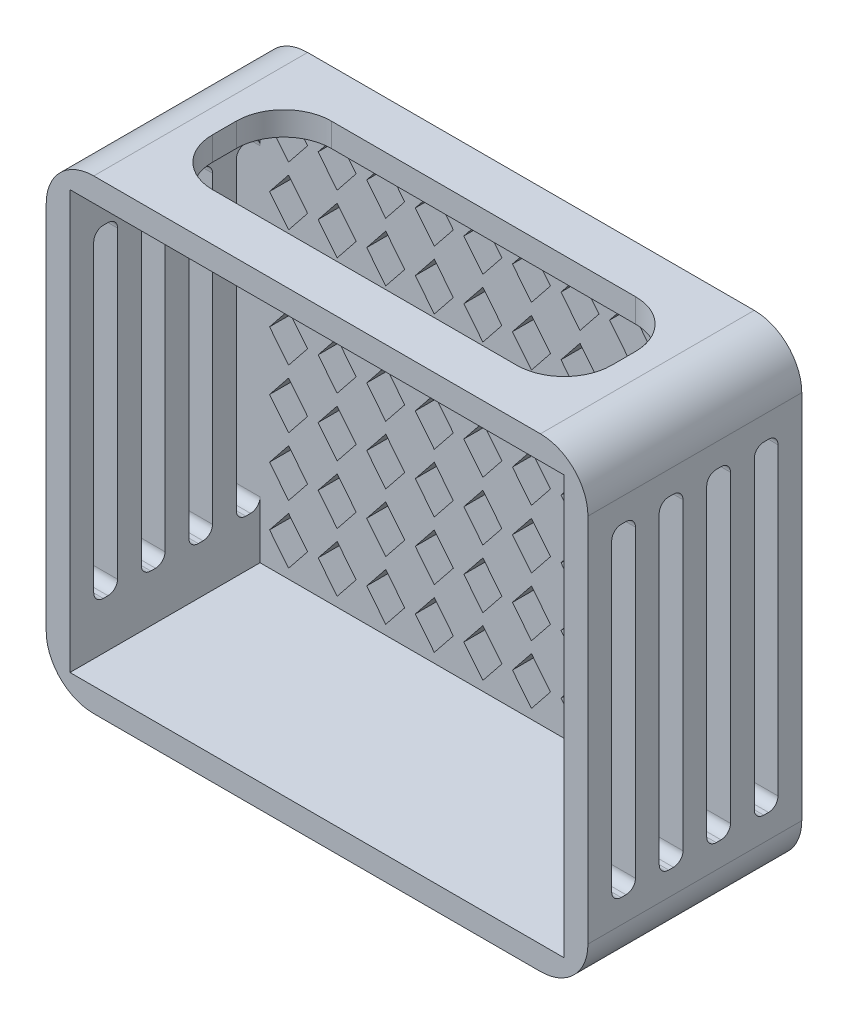
SolidWorks part; units mm, degrees
ref_plane "前视基准面" through (0, 0, 0) normal (0, 0, 1) x (1, 0, 0)
ref_plane "上视基准面" through (0, 0, 0) normal (0, 1, 0) x (1, 0, 0)
ref_plane "右视基准面" through (0, 0, 0) normal (1, 0, 0) x (0, 0, -1)
other "Configuration Table"
sketch "草图1" plane through (0, 0, 0) normal (0, 0, 1) x (1, 0, 0)
  line L1 (0, 98) -> (114, 98)
  line L2 (0, 98) -> (0, 0)
  line L3 (0, 0) -> (114, 0)
  line L4 (114, 98) -> (114, 0)
extrude "凸台-拉伸2" add sketch "草图1" against normal blind 45 contours L2 L1 L4 L3
sketch "草图3" plane through (0, 0, 0) normal (0, 0, 1) x (1, 0, 0)
  line L1 (5, 93) -> (109, 93)
  line L2 (5, 93) -> (5, 5)
  line L3 (5, 5) -> (109, 5)
  line L4 (109, 93) -> (109, 5)
  point P4 (0, 0)
extrude "切除-拉伸2" cut sketch "草图3" against normal blind 40
fillet "圆角1" radius 10 1 edges at (0, 98, -22.5)
fillet "圆角2" radius 10 1 edges at (0, 0, -22.5)
fillet "圆角3" radius 10 1 edges at (114, 0, -22.5)
fillet "圆角4" radius 10 1 edges at (114, 98, -22.5)
sketch "草图4" plane through (0, 98, 0) normal (0, 1, 0) x (1, 0, 0)
  line L0 (10, 45) -> (10, 0) construction
  line L1 (25, 35) -> (89, 35)
  line L2 (15, 25) -> (15, 20)
  line L3 (25, 10) -> (89, 10)
  line L4 (99, 25) -> (99, 20)
  line L5 (10, 45) -> (104, 45) construction
  line L6 (10, 0) -> (104, 0) construction
  line L7 (104, 0) -> (104, 45) construction
  arc A0 (99, 20) -> (89, 10) centre (89, 20) cw
  arc A1 (99, 25) -> (89, 35) centre (89, 25) ccw
  arc A2 (25, 10) -> (15, 20) centre (25, 20) cw
  arc A3 (25, 35) -> (15, 25) centre (25, 25) ccw
  dimension "D6" = 10
  dimension "D1" = 5
  dimension "D2" = 5
  dimension "D3" = 10
  dimension "D4" = 45
  dimension "D5" = 10
sketch "草图5" plane through (0, 0, -45) normal (0, 0, -1) x (-1, 0, 0)
  line L4 (-103, 91) -> (-107, 86)
  line L5 (-107, 86) -> (-103, 81)
  line L6 (-103, 81) -> (-99, 86)
  line L7 (-99, 86) -> (-103, 91)
  line L8 (-114, 88) -> (-114, 10) construction
  line L9 (0, 88) -> (0, 10) construction
  line L10 (-10, 98) -> (-104, 98) construction
  line L11 (-10, 0) -> (-104, 0) construction
  line L12 (-92.7778, 91) -> (-96.7778, 86)
  line L13 (-88.7778, 86) -> (-92.7778, 91)
  line L14 (-96.7778, 86) -> (-92.7778, 81)
  line L15 (-92.7778, 81) -> (-88.7778, 86)
  line L16 (-82.5556, 91) -> (-86.5556, 86)
  line L17 (-78.5556, 86) -> (-82.5556, 91)
  line L18 (-86.5556, 86) -> (-82.5556, 81)
  line L19 (-82.5556, 81) -> (-78.5556, 86)
  line L20 (-72.3333, 91) -> (-76.3333, 86)
  line L21 (-68.3333, 86) -> (-72.3333, 91)
  line L22 (-76.3333, 86) -> (-72.3333, 81)
  line L23 (-72.3333, 81) -> (-68.3333, 86)
  line L24 (-62.1111, 91) -> (-66.1111, 86)
  line L25 (-58.1111, 86) -> (-62.1111, 91)
  line L26 (-66.1111, 86) -> (-62.1111, 81)
  line L27 (-62.1111, 81) -> (-58.1111, 86)
  line L28 (-51.8889, 91) -> (-55.8889, 86)
  line L29 (-47.8889, 86) -> (-51.8889, 91)
  line L30 (-55.8889, 86) -> (-51.8889, 81)
  line L31 (-51.8889, 81) -> (-47.8889, 86)
  line L32 (-41.6667, 91) -> (-45.6667, 86)
  line L33 (-37.6667, 86) -> (-41.6667, 91)
  line L34 (-45.6667, 86) -> (-41.6667, 81)
  line L35 (-41.6667, 81) -> (-37.6667, 86)
  line L36 (-31.4444, 91) -> (-35.4444, 86)
  line L37 (-27.4444, 86) -> (-31.4444, 91)
  line L38 (-35.4444, 86) -> (-31.4444, 81)
  line L39 (-31.4444, 81) -> (-27.4444, 86)
  line L40 (-21.2222, 91) -> (-25.2222, 86)
  line L41 (-17.2222, 86) -> (-21.2222, 91)
  line L42 (-25.2222, 86) -> (-21.2222, 81)
  line L43 (-21.2222, 81) -> (-17.2222, 86)
  line L44 (-11, 91) -> (-15, 86)
  line L45 (-7, 86) -> (-11, 91)
  line L46 (-15, 86) -> (-11, 81)
  line L47 (-11, 81) -> (-7, 86)
  line L48 (-92.7778, 78.6667) -> (-96.7778, 73.6667)
  line L49 (-88.7778, 73.6667) -> (-92.7778, 78.6667)
  line L50 (-96.7778, 73.6667) -> (-92.7778, 68.6667)
  line L51 (-92.7778, 68.6667) -> (-88.7778, 73.6667)
  line L52 (-82.5556, 78.6667) -> (-86.5556, 73.6667)
  line L53 (-78.5556, 73.6667) -> (-82.5556, 78.6667)
  line L54 (-86.5556, 73.6667) -> (-82.5556, 68.6667)
  line L55 (-82.5556, 68.6667) -> (-78.5556, 73.6667)
  line L56 (-72.3333, 78.6667) -> (-76.3333, 73.6667)
  line L57 (-68.3333, 73.6667) -> (-72.3333, 78.6667)
  line L58 (-76.3333, 73.6667) -> (-72.3333, 68.6667)
  line L59 (-72.3333, 68.6667) -> (-68.3333, 73.6667)
  line L60 (-62.1111, 78.6667) -> (-66.1111, 73.6667)
  line L61 (-58.1111, 73.6667) -> (-62.1111, 78.6667)
  line L62 (-66.1111, 73.6667) -> (-62.1111, 68.6667)
  line L63 (-62.1111, 68.6667) -> (-58.1111, 73.6667)
  line L64 (-51.8889, 78.6667) -> (-55.8889, 73.6667)
  line L65 (-47.8889, 73.6667) -> (-51.8889, 78.6667)
  line L66 (-55.8889, 73.6667) -> (-51.8889, 68.6667)
  line L67 (-51.8889, 68.6667) -> (-47.8889, 73.6667)
  line L68 (-41.6667, 78.6667) -> (-45.6667, 73.6667)
  line L69 (-37.6667, 73.6667) -> (-41.6667, 78.6667)
  line L70 (-45.6667, 73.6667) -> (-41.6667, 68.6667)
  line L71 (-41.6667, 68.6667) -> (-37.6667, 73.6667)
  line L72 (-31.4444, 78.6667) -> (-35.4444, 73.6667)
  line L73 (-27.4444, 73.6667) -> (-31.4444, 78.6667)
  line L74 (-35.4444, 73.6667) -> (-31.4444, 68.6667)
  line L75 (-31.4444, 68.6667) -> (-27.4444, 73.6667)
  line L76 (-21.2222, 78.6667) -> (-25.2222, 73.6667)
  line L77 (-17.2222, 73.6667) -> (-21.2222, 78.6667)
  line L78 (-25.2222, 73.6667) -> (-21.2222, 68.6667)
  line L79 (-21.2222, 68.6667) -> (-17.2222, 73.6667)
  line L80 (-11, 78.6667) -> (-15, 73.6667)
  line L81 (-7, 73.6667) -> (-11, 78.6667)
  line L82 (-15, 73.6667) -> (-11, 68.6667)
  line L83 (-11, 68.6667) -> (-7, 73.6667)
  line L84 (-92.7778, 66.3333) -> (-96.7778, 61.3333)
  line L85 (-88.7778, 61.3333) -> (-92.7778, 66.3333)
  line L86 (-96.7778, 61.3333) -> (-92.7778, 56.3333)
  line L87 (-92.7778, 56.3333) -> (-88.7778, 61.3333)
  line L88 (-82.5556, 66.3333) -> (-86.5556, 61.3333)
  line L89 (-78.5556, 61.3333) -> (-82.5556, 66.3333)
  line L90 (-86.5556, 61.3333) -> (-82.5556, 56.3333)
  line L91 (-82.5556, 56.3333) -> (-78.5556, 61.3333)
  line L92 (-72.3333, 66.3333) -> (-76.3333, 61.3333)
  line L93 (-68.3333, 61.3333) -> (-72.3333, 66.3333)
  line L94 (-76.3333, 61.3333) -> (-72.3333, 56.3333)
  line L95 (-72.3333, 56.3333) -> (-68.3333, 61.3333)
  line L96 (-62.1111, 66.3333) -> (-66.1111, 61.3333)
  line L97 (-58.1111, 61.3333) -> (-62.1111, 66.3333)
  line L98 (-66.1111, 61.3333) -> (-62.1111, 56.3333)
  line L99 (-62.1111, 56.3333) -> (-58.1111, 61.3333)
  line L100 (-51.8889, 66.3333) -> (-55.8889, 61.3333)
  line L101 (-47.8889, 61.3333) -> (-51.8889, 66.3333)
  line L102 (-55.8889, 61.3333) -> (-51.8889, 56.3333)
  line L103 (-51.8889, 56.3333) -> (-47.8889, 61.3333)
  line L104 (-41.6667, 66.3333) -> (-45.6667, 61.3333)
  line L105 (-37.6667, 61.3333) -> (-41.6667, 66.3333)
  line L106 (-45.6667, 61.3333) -> (-41.6667, 56.3333)
  line L107 (-41.6667, 56.3333) -> (-37.6667, 61.3333)
  line L108 (-31.4444, 66.3333) -> (-35.4444, 61.3333)
  line L109 (-27.4444, 61.3333) -> (-31.4444, 66.3333)
  line L110 (-35.4444, 61.3333) -> (-31.4444, 56.3333)
  line L111 (-31.4444, 56.3333) -> (-27.4444, 61.3333)
  line L112 (-21.2222, 66.3333) -> (-25.2222, 61.3333)
  line L113 (-17.2222, 61.3333) -> (-21.2222, 66.3333)
  line L114 (-25.2222, 61.3333) -> (-21.2222, 56.3333)
  line L115 (-21.2222, 56.3333) -> (-17.2222, 61.3333)
  line L116 (-11, 66.3333) -> (-15, 61.3333)
  line L117 (-7, 61.3333) -> (-11, 66.3333)
  line L118 (-15, 61.3333) -> (-11, 56.3333)
  line L119 (-11, 56.3333) -> (-7, 61.3333)
  line L120 (-92.7778, 54) -> (-96.7778, 49)
  line L121 (-88.7778, 49) -> (-92.7778, 54)
  line L122 (-96.7778, 49) -> (-92.7778, 44)
  line L123 (-92.7778, 44) -> (-88.7778, 49)
  line L124 (-82.5556, 54) -> (-86.5556, 49)
  line L125 (-78.5556, 49) -> (-82.5556, 54)
  line L126 (-86.5556, 49) -> (-82.5556, 44)
  line L127 (-82.5556, 44) -> (-78.5556, 49)
  line L128 (-72.3333, 54) -> (-76.3333, 49)
  line L129 (-68.3333, 49) -> (-72.3333, 54)
  line L130 (-76.3333, 49) -> (-72.3333, 44)
  line L131 (-72.3333, 44) -> (-68.3333, 49)
  line L132 (-62.1111, 54) -> (-66.1111, 49)
  line L133 (-58.1111, 49) -> (-62.1111, 54)
  line L134 (-66.1111, 49) -> (-62.1111, 44)
  line L135 (-62.1111, 44) -> (-58.1111, 49)
  line L136 (-51.8889, 54) -> (-55.8889, 49)
  line L137 (-47.8889, 49) -> (-51.8889, 54)
  line L138 (-55.8889, 49) -> (-51.8889, 44)
  line L139 (-51.8889, 44) -> (-47.8889, 49)
  line L140 (-41.6667, 54) -> (-45.6667, 49)
  line L141 (-37.6667, 49) -> (-41.6667, 54)
  line L142 (-45.6667, 49) -> (-41.6667, 44)
  line L143 (-41.6667, 44) -> (-37.6667, 49)
  line L144 (-31.4444, 54) -> (-35.4444, 49)
  line L145 (-27.4444, 49) -> (-31.4444, 54)
  line L146 (-35.4444, 49) -> (-31.4444, 44)
  line L147 (-31.4444, 44) -> (-27.4444, 49)
  line L148 (-21.2222, 54) -> (-25.2222, 49)
  line L149 (-17.2222, 49) -> (-21.2222, 54)
  line L150 (-25.2222, 49) -> (-21.2222, 44)
  line L151 (-21.2222, 44) -> (-17.2222, 49)
  line L152 (-11, 54) -> (-15, 49)
  line L153 (-7, 49) -> (-11, 54)
  line L154 (-15, 49) -> (-11, 44)
  line L155 (-11, 44) -> (-7, 49)
  line L156 (-92.7778, 41.6667) -> (-96.7778, 36.6667)
  line L157 (-88.7778, 36.6667) -> (-92.7778, 41.6667)
  line L158 (-96.7778, 36.6667) -> (-92.7778, 31.6667)
  line L159 (-92.7778, 31.6667) -> (-88.7778, 36.6667)
  line L160 (-82.5556, 41.6667) -> (-86.5556, 36.6667)
  line L161 (-78.5556, 36.6667) -> (-82.5556, 41.6667)
  line L162 (-86.5556, 36.6667) -> (-82.5556, 31.6667)
  line L163 (-82.5556, 31.6667) -> (-78.5556, 36.6667)
  line L164 (-72.3333, 41.6667) -> (-76.3333, 36.6667)
  line L165 (-68.3333, 36.6667) -> (-72.3333, 41.6667)
  line L166 (-76.3333, 36.6667) -> (-72.3333, 31.6667)
  line L167 (-72.3333, 31.6667) -> (-68.3333, 36.6667)
  line L168 (-62.1111, 41.6667) -> (-66.1111, 36.6667)
  line L169 (-58.1111, 36.6667) -> (-62.1111, 41.6667)
  line L170 (-66.1111, 36.6667) -> (-62.1111, 31.6667)
  line L171 (-62.1111, 31.6667) -> (-58.1111, 36.6667)
  line L172 (-51.8889, 41.6667) -> (-55.8889, 36.6667)
  line L173 (-47.8889, 36.6667) -> (-51.8889, 41.6667)
  line L174 (-55.8889, 36.6667) -> (-51.8889, 31.6667)
  line L175 (-51.8889, 31.6667) -> (-47.8889, 36.6667)
  line L176 (-41.6667, 41.6667) -> (-45.6667, 36.6667)
  line L177 (-37.6667, 36.6667) -> (-41.6667, 41.6667)
  line L178 (-45.6667, 36.6667) -> (-41.6667, 31.6667)
  line L179 (-41.6667, 31.6667) -> (-37.6667, 36.6667)
  line L180 (-31.4444, 41.6667) -> (-35.4444, 36.6667)
  line L181 (-27.4444, 36.6667) -> (-31.4444, 41.6667)
  line L182 (-35.4444, 36.6667) -> (-31.4444, 31.6667)
  line L183 (-31.4444, 31.6667) -> (-27.4444, 36.6667)
  line L184 (-21.2222, 41.6667) -> (-25.2222, 36.6667)
  line L185 (-17.2222, 36.6667) -> (-21.2222, 41.6667)
  line L186 (-25.2222, 36.6667) -> (-21.2222, 31.6667)
  line L187 (-21.2222, 31.6667) -> (-17.2222, 36.6667)
  line L188 (-11, 41.6667) -> (-15, 36.6667)
  line L189 (-7, 36.6667) -> (-11, 41.6667)
  line L190 (-15, 36.6667) -> (-11, 31.6667)
  line L191 (-11, 31.6667) -> (-7, 36.6667)
  line L192 (-92.7778, 29.3333) -> (-96.7778, 24.3333)
  line L193 (-88.7778, 24.3333) -> (-92.7778, 29.3333)
  line L194 (-96.7778, 24.3333) -> (-92.7778, 19.3333)
  line L195 (-92.7778, 19.3333) -> (-88.7778, 24.3333)
  line L196 (-82.5556, 29.3333) -> (-86.5556, 24.3333)
  line L197 (-78.5556, 24.3333) -> (-82.5556, 29.3333)
  line L198 (-86.5556, 24.3333) -> (-82.5556, 19.3333)
  line L199 (-82.5556, 19.3333) -> (-78.5556, 24.3333)
  line L200 (-72.3333, 29.3333) -> (-76.3333, 24.3333)
  line L201 (-68.3333, 24.3333) -> (-72.3333, 29.3333)
  line L202 (-76.3333, 24.3333) -> (-72.3333, 19.3333)
  line L203 (-72.3333, 19.3333) -> (-68.3333, 24.3333)
  line L204 (-62.1111, 29.3333) -> (-66.1111, 24.3333)
  line L205 (-58.1111, 24.3333) -> (-62.1111, 29.3333)
  line L206 (-66.1111, 24.3333) -> (-62.1111, 19.3333)
  line L207 (-62.1111, 19.3333) -> (-58.1111, 24.3333)
  line L208 (-51.8889, 29.3333) -> (-55.8889, 24.3333)
  line L209 (-47.8889, 24.3333) -> (-51.8889, 29.3333)
  line L210 (-55.8889, 24.3333) -> (-51.8889, 19.3333)
  line L211 (-51.8889, 19.3333) -> (-47.8889, 24.3333)
  line L212 (-41.6667, 29.3333) -> (-45.6667, 24.3333)
  line L213 (-37.6667, 24.3333) -> (-41.6667, 29.3333)
  line L214 (-45.6667, 24.3333) -> (-41.6667, 19.3333)
  line L215 (-41.6667, 19.3333) -> (-37.6667, 24.3333)
  line L216 (-31.4444, 29.3333) -> (-35.4444, 24.3333)
  line L217 (-27.4444, 24.3333) -> (-31.4444, 29.3333)
  line L218 (-35.4444, 24.3333) -> (-31.4444, 19.3333)
  line L219 (-31.4444, 19.3333) -> (-27.4444, 24.3333)
  line L220 (-21.2222, 29.3333) -> (-25.2222, 24.3333)
  line L221 (-17.2222, 24.3333) -> (-21.2222, 29.3333)
  line L222 (-25.2222, 24.3333) -> (-21.2222, 19.3333)
  line L223 (-21.2222, 19.3333) -> (-17.2222, 24.3333)
  line L224 (-11, 29.3333) -> (-15, 24.3333)
  line L225 (-7, 24.3333) -> (-11, 29.3333)
  line L226 (-15, 24.3333) -> (-11, 19.3333)
  line L227 (-11, 19.3333) -> (-7, 24.3333)
  line L228 (-92.7778, 17) -> (-96.7778, 12)
  line L229 (-88.7778, 12) -> (-92.7778, 17)
  line L230 (-96.7778, 12) -> (-92.7778, 7)
  line L231 (-92.7778, 7) -> (-88.7778, 12)
  line L232 (-82.5556, 17) -> (-86.5556, 12)
  line L233 (-78.5556, 12) -> (-82.5556, 17)
  line L234 (-86.5556, 12) -> (-82.5556, 7)
  line L235 (-82.5556, 7) -> (-78.5556, 12)
  line L236 (-72.3333, 17) -> (-76.3333, 12)
  line L237 (-68.3333, 12) -> (-72.3333, 17)
  line L238 (-76.3333, 12) -> (-72.3333, 7)
  line L239 (-72.3333, 7) -> (-68.3333, 12)
  line L240 (-62.1111, 17) -> (-66.1111, 12)
  line L241 (-58.1111, 12) -> (-62.1111, 17)
  line L242 (-66.1111, 12) -> (-62.1111, 7)
  line L243 (-62.1111, 7) -> (-58.1111, 12)
  line L244 (-51.8889, 17) -> (-55.8889, 12)
  line L245 (-47.8889, 12) -> (-51.8889, 17)
  line L246 (-55.8889, 12) -> (-51.8889, 7)
  line L247 (-51.8889, 7) -> (-47.8889, 12)
  line L248 (-41.6667, 17) -> (-45.6667, 12)
  line L249 (-37.6667, 12) -> (-41.6667, 17)
  line L250 (-45.6667, 12) -> (-41.6667, 7)
  line L251 (-41.6667, 7) -> (-37.6667, 12)
  line L252 (-31.4444, 17) -> (-35.4444, 12)
  line L253 (-27.4444, 12) -> (-31.4444, 17)
  line L254 (-35.4444, 12) -> (-31.4444, 7)
  line L255 (-31.4444, 7) -> (-27.4444, 12)
  line L256 (-21.2222, 17) -> (-25.2222, 12)
  line L257 (-17.2222, 12) -> (-21.2222, 17)
  line L258 (-25.2222, 12) -> (-21.2222, 7)
  line L259 (-21.2222, 7) -> (-17.2222, 12)
  line L260 (-11, 17) -> (-15, 12)
  line L261 (-7, 12) -> (-11, 17)
  line L262 (-15, 12) -> (-11, 7)
  line L263 (-11, 7) -> (-7, 12)
  line L264 (-103, 78.6667) -> (-107, 73.6667)
  line L265 (-99, 73.6667) -> (-103, 78.6667)
  line L266 (-107, 73.6667) -> (-103, 68.6667)
  line L267 (-103, 68.6667) -> (-99, 73.6667)
  line L268 (-103, 66.3333) -> (-107, 61.3333)
  line L269 (-99, 61.3333) -> (-103, 66.3333)
  line L270 (-107, 61.3333) -> (-103, 56.3333)
  line L271 (-103, 56.3333) -> (-99, 61.3333)
  line L272 (-103, 54) -> (-107, 49)
  line L273 (-99, 49) -> (-103, 54)
  line L274 (-107, 49) -> (-103, 44)
  line L275 (-103, 44) -> (-99, 49)
  line L276 (-103, 41.6667) -> (-107, 36.6667)
  line L277 (-99, 36.6667) -> (-103, 41.6667)
  line L278 (-107, 36.6667) -> (-103, 31.6667)
  line L279 (-103, 31.6667) -> (-99, 36.6667)
  line L280 (-103, 29.3333) -> (-107, 24.3333)
  line L281 (-99, 24.3333) -> (-103, 29.3333)
  line L282 (-107, 24.3333) -> (-103, 19.3333)
  line L283 (-103, 19.3333) -> (-99, 24.3333)
  line L284 (-103, 17) -> (-107, 12)
  line L285 (-99, 12) -> (-103, 17)
  line L286 (-107, 12) -> (-103, 7)
  line L287 (-103, 7) -> (-99, 12)
  point P2 (0, 0)
  dimension "D1" = 8
  dimension "D2" = 114
  dimension "D3" = 7
  dimension "D4" = 7
  dimension "D5" = 10
  dimension "D6" = 98
  dimension "D7" = 10
  dimension "D9" = 7
  dimension "D10" = 7
  dimension "D8" = 7
extrude "切除-拉伸3" cut sketch "草图5" against normal blind 10
extrude "切除-拉伸4" cut sketch "草图4" against normal blind 10
sketch "草图6" plane through (114, 0, 0) normal (1, 0, 0) x (0, 0, -1)
  line L0 (0, 88) -> (0, 10) construction
  line L5 (45, 88) -> (45, 10) construction
  line L6 (45, 88) -> (0, 88) construction
  line L7 (0, 10) -> (45, 10) construction
  line L29 (15, 81) -> (15, 17)
  line L30 (7, 83) -> (8, 83)
  line L31 (5, 81) -> (5, 17)
  line L32 (7, 15) -> (8, 15)
  line L33 (10, 81) -> (10, 17)
  line L34 (17, 83) -> (18, 83)
  line L35 (20, 81) -> (20, 17)
  line L36 (17, 15) -> (18, 15)
  line L37 (25, 81) -> (25, 17)
  line L38 (27, 83) -> (28, 83)
  line L39 (30, 81) -> (30, 17)
  line L40 (27, 15) -> (28, 15)
  line L41 (35, 81) -> (35, 17)
  line L42 (37, 83) -> (38, 83)
  line L43 (40, 81) -> (40, 17)
  line L44 (37, 15) -> (38, 15)
  line L45 (5, 83) -> (15, 83) construction
  arc A16 (37, 83) -> (35, 81) centre (37, 81) ccw
  arc A17 (40, 81) -> (38, 83) centre (38, 81) ccw
  arc A18 (40, 17) -> (38, 15) centre (38, 17) cw
  arc A19 (37, 15) -> (35, 17) centre (37, 17) cw
  arc A20 (30, 17) -> (28, 15) centre (28, 17) cw
  arc A21 (27, 15) -> (25, 17) centre (27, 17) cw
  arc A22 (28, 83) -> (30, 81) centre (28, 81) cw
  arc A23 (27, 83) -> (25, 81) centre (27, 81) ccw
  arc A24 (20, 81) -> (18, 83) centre (18, 81) ccw
  arc A25 (17, 83) -> (15, 81) centre (17, 81) ccw
  arc A26 (20, 17) -> (18, 15) centre (18, 17) cw
  arc A27 (17, 15) -> (15, 17) centre (17, 17) cw
  arc A28 (8, 15) -> (10, 17) centre (8, 17) ccw
  arc A29 (7, 15) -> (5, 17) centre (7, 17) cw
  arc A30 (8, 83) -> (10, 81) centre (8, 81) cw
  arc A31 (7, 83) -> (5, 81) centre (7, 81) ccw
  point P46 (15, 83)
  point P77 (5, 83)
  dimension "D7" = 4
  dimension "D9" = 2
  dimension "D1" = 5
  dimension "D2" = 45
  dimension "D3" = 5
  dimension "D4" = 78
  dimension "D5" = 5
  dimension "D6" = 10
  dimension "D8" = 5
extrude "切除-拉伸5" cut sketch "草图6" against normal blind 150
